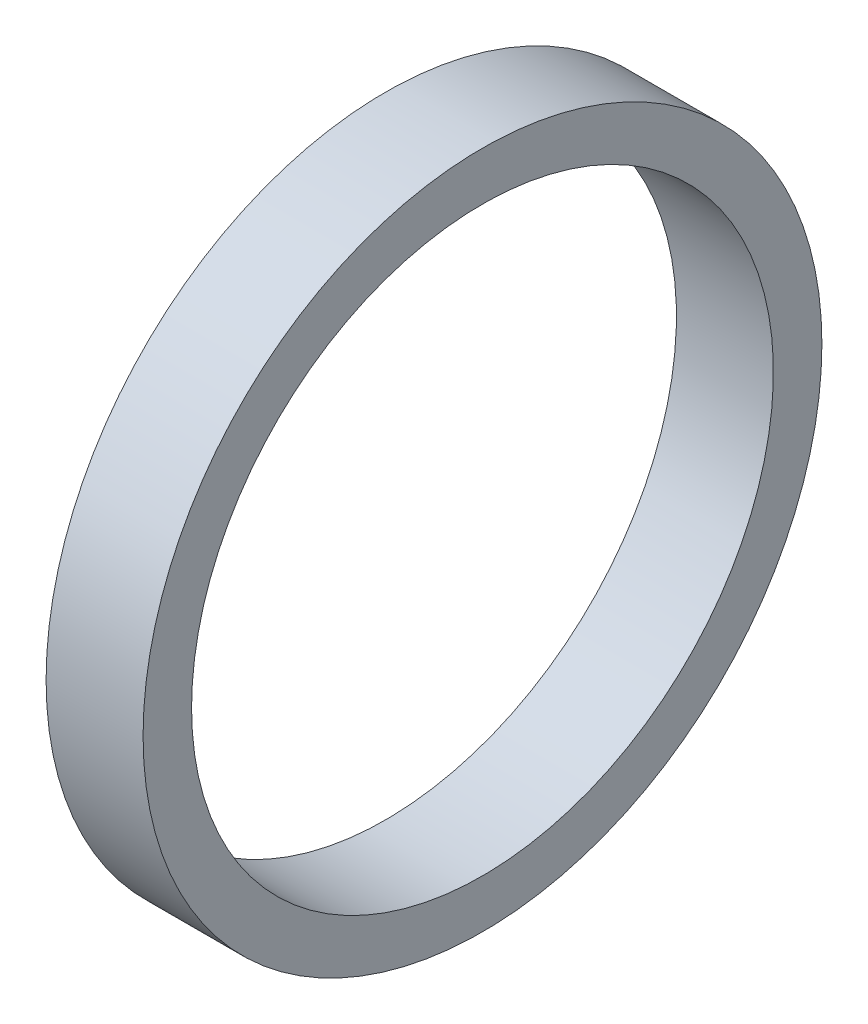
SolidWorks part; units mm, degrees
ref_plane "Front Plane" through (0, 0, 0) normal (0, 0, 1) x (1, 0, 0)
ref_plane "Top Plane" through (0, 0, 0) normal (0, 1, 0) x (1, 0, 0)
ref_plane "Right Plane" through (0, 0, 0) normal (1, 0, 0) x (0, 0, -1)
sketch "Sketch1" plane through (0, 0, 0) normal (0, 0, 1) x (1, 0, 0)
  line L0 (0, 6) -> (2, 6)
  line L1 (2, 6) -> (2, 7)
  line L2 (2, 7) -> (0, 7)
  line L3 (0, 7) -> (0, 6)
  line L4 (0, 0) -> (21.6923, 0) construction
  dimension "D1" = 6
  dimension "D2" = 7
  dimension "D3" = 2
revolve "Revolve1" add sketch "Sketch1" angle 360 about L4
